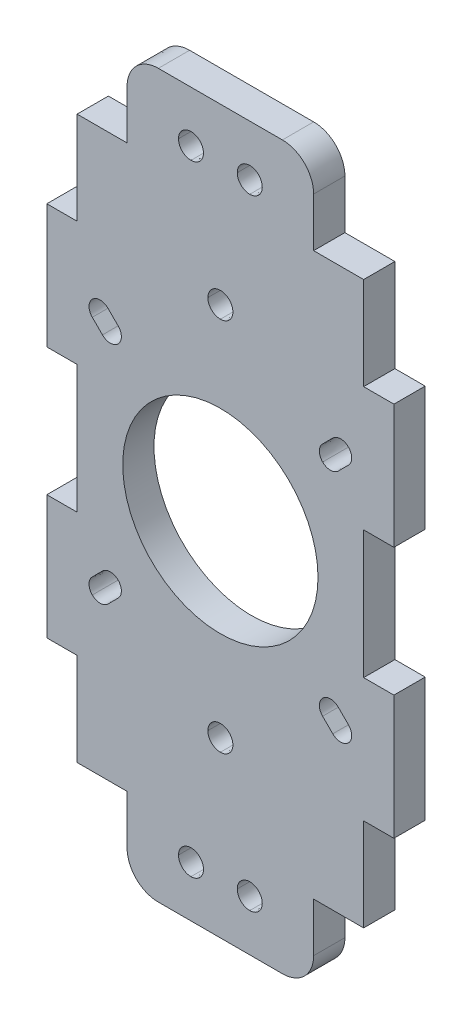
SolidWorks part; units mm, degrees
ref_plane "Front Plane" through (0, 0, 0) normal (0, 0, 1) x (1, 0, 0)
ref_plane "Top Plane" through (0, 0, 0) normal (0, 1, 0) x (1, 0, 0)
ref_plane "Right Plane" through (0, 0, 0) normal (1, 0, 0) x (0, 0, -1)
sketch "Model" plane through (0, 0, 0) normal (0, 0, 1) x (1, 0, 0)
  line L221 (-20.5954, 56.0124) -> (-20.5954, 81.2129)
  line L225 (-20.5954, 107.2136) -> (-20.5954, 132.4124)
  line L234 (49.9256, 132.4124) -> (43.7754, 132.4124)
  line L235 (43.7754, 132.4124) -> (43.7754, 151.262)
  line L236 (43.7754, 151.262) -> (33.6151, 151.262)
  line L237 (33.6151, 151.262) -> (33.6151, 161.223)
  line L238 (27.2651, 167.573) -> (2.0647, 167.573)
  line L239 (-4.2849, 161.223) -> (-4.2849, 151.262)
  line L240 (-4.2849, 151.262) -> (-14.4452, 151.262)
  line L241 (-14.4452, 151.262) -> (-14.4452, 132.4124)
  line L242 (-14.4452, 132.4124) -> (-20.5954, 132.4124)
  line L244 (-20.5954, 107.2136) -> (-14.4452, 107.2136)
  line L245 (-14.4452, 107.2136) -> (-14.4452, 81.2129)
  line L246 (-14.4452, 81.2129) -> (-20.5954, 81.2129)
  line L248 (-20.5954, 56.0124) -> (-14.4452, 56.0124)
  line L249 (-14.4452, 56.0124) -> (-14.4452, 37.1628)
  line L250 (-14.4452, 37.1628) -> (-4.2849, 37.1628)
  line L251 (-4.2849, 37.1628) -> (-4.2849, 27.2034)
  line L252 (2.0647, 20.8535) -> (27.2651, 20.8535)
  line L253 (33.6151, 27.2034) -> (33.6151, 37.1628)
  line L254 (33.6151, 37.1628) -> (43.7754, 37.1628)
  line L255 (43.7754, 37.1628) -> (43.7754, 56.0124)
  line L256 (43.7754, 56.0124) -> (49.9256, 56.0124)
  line L257 (49.9256, 56.0124) -> (49.9256, 81.2129)
  line L258 (49.9256, 81.2129) -> (43.7754, 81.2129)
  line L259 (43.7754, 81.2129) -> (43.7754, 107.2136)
  line L260 (43.7754, 107.2136) -> (49.9256, 107.2136)
  line L261 (49.9256, 107.2136) -> (49.9256, 132.4124)
  line L262 (-6.1122, 70.2543) -> (-8.1775, 68.1903)
  line L263 (-11.3583, 71.3711) -> (-9.293, 73.4364)
  line L264 (40.6885, 117.0554) -> (38.6232, 114.9897)
  line L265 (35.4411, 118.1717) -> (37.5068, 120.2357)
  line L266 (40.6885, 71.3707) -> (38.6227, 73.4364)
  line L267 (35.4411, 70.2547) -> (37.5068, 68.1903)
  line L268 (-6.1122, 118.1717) -> (-8.1766, 120.2357)
  line L269 (-11.3583, 117.0554) -> (-9.2926, 114.9897)
  circle A0 centre (14.6645, 94.2133) radius 19.8395
  spline S480 degree 3 poles (33.6151, 161.223) (33.6151, 164.741) (30.7835, 167.573) (27.2651, 167.573) knots 0.121212 0.121212 0.121212 0.121212 0.151515 0.151515 0.151515 0.151515
  spline S481 degree 3 poles (2.0647, 167.573) (-1.4529, 167.573) (-4.2849, 164.741) (-4.2849, 161.223) knots 0.181818 0.181818 0.181818 0.181818 0.212121 0.212121 0.212121 0.212121
  spline S482 degree 3 poles (-4.2849, 27.2034) (-4.2849, 23.6854) (-1.4529, 20.8535) (2.0647, 20.8535) knots 0.606061 0.606061 0.606061 0.606061 0.636364 0.636364 0.636364 0.636364
  spline S483 degree 3 poles (27.2651, 20.8535) (30.7835, 20.8535) (33.6151, 23.6854) (33.6151, 27.2034) knots 0.666667 0.666667 0.666667 0.666667 0.69697 0.69697 0.69697 0.69697
  spline S484 degree 3 poles (8.6945, 154.6937) (10.0978, 154.6937) (11.2349, 155.8307) (11.2349, 157.2336) knots 0 0 0 0 0.2 0.2 0.2 0.2
  spline S485 degree 3 poles (11.2349, 157.2336) (11.2349, 158.6365) (10.0978, 159.7728) (8.6945, 159.7728) knots 0.2 0.2 0.2 0.2 0.4 0.4 0.4 0.4
  spline S486 degree 3 poles (8.6945, 159.7728) (7.2921, 159.7728) (6.1537, 158.6365) (6.1537, 157.2336) knots 0.4 0.4 0.4 0.4 0.6 0.6 0.6 0.6
  spline S487 degree 3 poles (6.1537, 157.2336) (6.1537, 155.8307) (7.2921, 154.6937) (8.6945, 154.6937) knots 0.6 0.6 0.6 0.6 1 1 1 1
  spline S488 degree 3 poles (8.6945, 28.6532) (10.0978, 28.6532) (11.2349, 29.7899) (11.2349, 31.1928) knots 0 0 0 0 0.2 0.2 0.2 0.2
  spline S489 degree 3 poles (11.2349, 31.1928) (11.2349, 32.5953) (10.0978, 33.7324) (8.6945, 33.7324) knots 0.2 0.2 0.2 0.2 0.4 0.4 0.4 0.4
  spline S490 degree 3 poles (8.6945, 33.7324) (7.2921, 33.7324) (6.1537, 32.5953) (6.1537, 31.1928) knots 0.4 0.4 0.4 0.4 0.6 0.6 0.6 0.6
  spline S491 degree 3 poles (6.1537, 31.1928) (6.1537, 29.7899) (7.2921, 28.6532) (8.6945, 28.6532) knots 0.6 0.6 0.6 0.6 1 1 1 1
  spline S492 degree 3 poles (-8.1775, 68.1903) (-9.0583, 67.3086) (-10.4778, 67.3086) (-11.3583, 68.1903) knots 0.142857 0.142857 0.142857 0.142857 0.285714 0.285714 0.285714 0.285714
  spline S493 degree 3 poles (-11.3583, 68.1903) (-12.2399, 69.0707) (-12.2399, 70.4906) (-11.3583, 71.3711) knots 0.285714 0.285714 0.285714 0.285714 0.428571 0.428571 0.428571 0.428571
  spline S494 degree 3 poles (-9.293, 73.4364) (-8.4121, 74.3185) (-6.9926, 74.3185) (-6.1122, 73.4364) knots 0.571429 0.571429 0.571429 0.571429 0.714286 0.714286 0.714286 0.714286
  spline S495 degree 3 poles (-6.1122, 73.4364) (-5.2301, 72.5559) (-5.2301, 71.1364) (-6.1122, 70.2543) knots 0.714286 0.714286 0.714286 0.714286 1 1 1 1
  spline S496 degree 3 poles (38.6232, 114.9897) (37.7415, 114.1092) (36.3232, 114.1092) (35.4411, 114.9897) knots 0.142857 0.142857 0.142857 0.142857 0.285714 0.285714 0.285714 0.285714
  spline S497 degree 3 poles (35.4411, 114.9897) (34.5607, 115.8705) (34.5607, 117.29) (35.4411, 118.1717) knots 0.285714 0.285714 0.285714 0.285714 0.428571 0.428571 0.428571 0.428571
  spline S498 degree 3 poles (37.5068, 120.2357) (38.3885, 121.1178) (39.8068, 121.1178) (40.6889, 120.2357) knots 0.571429 0.571429 0.571429 0.571429 0.714286 0.714286 0.714286 0.714286
  spline S499 degree 3 poles (40.6889, 120.2357) (41.5693, 119.3553) (41.5693, 117.9358) (40.6885, 117.0554) knots 0.714286 0.714286 0.714286 0.714286 1 1 1 1
  spline S500 degree 3 poles (38.6227, 73.4364) (37.7411, 74.3185) (36.3228, 74.3185) (35.4407, 73.4364) knots 0.142857 0.142857 0.142857 0.142857 0.285714 0.285714 0.285714 0.285714
  spline S501 degree 3 poles (35.4407, 73.4364) (34.5603, 72.5559) (34.5607, 71.1368) (35.4411, 70.2547) knots 0.285714 0.285714 0.285714 0.285714 0.428571 0.428571 0.428571 0.428571
  spline S502 degree 3 poles (37.5068, 68.1903) (38.3889, 67.3086) (39.8064, 67.3086) (40.6885, 68.1903) knots 0.571429 0.571429 0.571429 0.571429 0.714286 0.714286 0.714286 0.714286
  spline S503 degree 3 poles (40.6885, 68.1903) (41.5689, 69.0707) (41.5693, 70.4902) (40.6885, 71.3707) knots 0.714286 0.714286 0.714286 0.714286 1 1 1 1
  spline S504 degree 3 poles (-8.1766, 120.2357) (-9.0587, 121.1178) (-10.4782, 121.1178) (-11.3587, 120.2357) knots 0.142857 0.142857 0.142857 0.142857 0.285714 0.285714 0.285714 0.285714
  spline S505 degree 3 poles (-11.3587, 120.2357) (-12.2391, 119.3553) (-12.2387, 117.9362) (-11.3583, 117.0554) knots 0.285714 0.285714 0.285714 0.285714 0.428571 0.428571 0.428571 0.428571
  spline S506 degree 3 poles (-9.2926, 114.9897) (-8.4121, 114.1076) (-6.993, 114.1076) (-6.1126, 114.9897) knots 0.571429 0.571429 0.571429 0.571429 0.714286 0.714286 0.714286 0.714286
  spline S507 degree 3 poles (-6.1126, 114.9897) (-5.2305, 115.8705) (-5.2301, 117.2896) (-6.1122, 118.1717) knots 0.714286 0.714286 0.714286 0.714286 1 1 1 1
  spline S508 degree 3 poles (20.6352, 154.6937) (22.0385, 154.6937) (23.1752, 155.8307) (23.1752, 157.2336) knots 0 0 0 0 0.2 0.2 0.2 0.2
  spline S509 degree 3 poles (23.1752, 157.2336) (23.1752, 158.6365) (22.0385, 159.7728) (20.6352, 159.7728) knots 0.2 0.2 0.2 0.2 0.4 0.4 0.4 0.4
  spline S510 degree 3 poles (20.6352, 159.7728) (19.2328, 159.7728) (18.0957, 158.6365) (18.0957, 157.2336) knots 0.4 0.4 0.4 0.4 0.6 0.6 0.6 0.6
  spline S511 degree 3 poles (18.0957, 157.2336) (18.0957, 155.8307) (19.2328, 154.6937) (20.6352, 154.6937) knots 0.6 0.6 0.6 0.6 1 1 1 1
  spline S512 degree 3 poles (20.6352, 28.6532) (22.0385, 28.6532) (23.1752, 29.7899) (23.1752, 31.1928) knots 0 0 0 0 0.2 0.2 0.2 0.2
  spline S513 degree 3 poles (23.1752, 31.1928) (23.1752, 32.5953) (22.0385, 33.7324) (20.6352, 33.7324) knots 0.2 0.2 0.2 0.2 0.4 0.4 0.4 0.4
  spline S514 degree 3 poles (20.6352, 33.7324) (19.2328, 33.7324) (18.0957, 32.5953) (18.0957, 31.1928) knots 0.4 0.4 0.4 0.4 0.6 0.6 0.6 0.6
  spline S515 degree 3 poles (18.0957, 31.1928) (18.0957, 29.7899) (19.2328, 28.6532) (20.6352, 28.6532) knots 0.6 0.6 0.6 0.6 1 1 1 1
  spline S516 degree 3 poles (14.6645, 129.7262) (16.0674, 129.7262) (17.2053, 130.8633) (17.2053, 132.2662) knots 0 0 0 0 0.2 0.2 0.2 0.2
  spline S517 degree 3 poles (17.2053, 132.2662) (17.2053, 133.6691) (16.0674, 134.8074) (14.6645, 134.8074) knots 0.2 0.2 0.2 0.2 0.4 0.4 0.4 0.4
  spline S518 degree 3 poles (14.6645, 134.8074) (13.2616, 134.8074) (12.1245, 133.6691) (12.1245, 132.2662) knots 0.4 0.4 0.4 0.4 0.6 0.6 0.6 0.6
  spline S519 degree 3 poles (12.1245, 132.2662) (12.1245, 130.8633) (13.2616, 129.7262) (14.6645, 129.7262) knots 0.6 0.6 0.6 0.6 1 1 1 1
  spline S520 degree 3 poles (14.6645, 53.5264) (16.0674, 53.5264) (17.2053, 54.6635) (17.2053, 56.0664) knots 0 0 0 0 0.2 0.2 0.2 0.2
  spline S521 degree 3 poles (17.2053, 56.0664) (17.2053, 57.4693) (16.0674, 58.6076) (14.6645, 58.6076) knots 0.2 0.2 0.2 0.2 0.4 0.4 0.4 0.4
  spline S522 degree 3 poles (14.6645, 58.6076) (13.2616, 58.6076) (12.1245, 57.4693) (12.1245, 56.0664) knots 0.4 0.4 0.4 0.4 0.6 0.6 0.6 0.6
  spline S523 degree 3 poles (12.1245, 56.0664) (12.1245, 54.6635) (13.2616, 53.5264) (14.6645, 53.5264) knots 0.6 0.6 0.6 0.6 1 1 1 1
  point P3 (14.6645, 114.0528)
extrude "Boss-Extrude1" add sketch "Model" along normal blind 6.35
